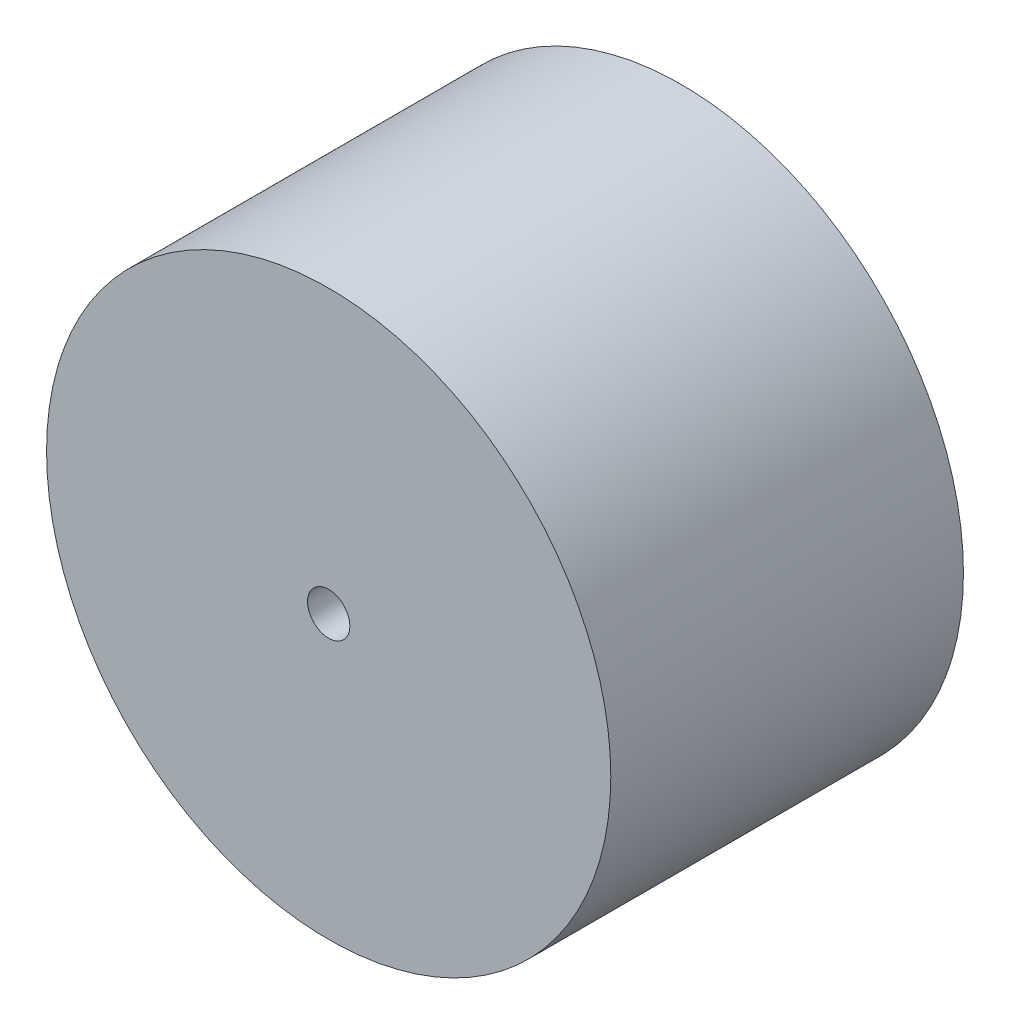
SolidWorks part; units mm, degrees
ref_plane "前视基准面" through (0, 0, 0) normal (0, 0, 1) x (1, 0, 0)
ref_plane "上视基准面" through (0, 0, 0) normal (0, 1, 0) x (1, 0, 0)
ref_plane "右视基准面" through (0, 0, 0) normal (1, 0, 0) x (0, 0, -1)
other "Configuration Table"
sketch "草图1" plane through (0, 0, 0) normal (0, 0, 1) x (1, 0, 0)
  circle A0 centre (0, 0) radius 40
  dimension "D1" = 80
extrude "凸台-拉伸1" add sketch "草图1" along normal blind 50
sketch "草图2" plane through (0, 0, 50) normal (0, 0, 1) x (1, 0, 0)
  circle A0 centre (0, 0) radius 3
  dimension "D1" = 6
extrude "切除-拉伸1" cut sketch "草图2" against normal through all
ref_plane "基准面1" through (0, 0, 25) normal (0, 0, -1) x (-1, 0, 0)
